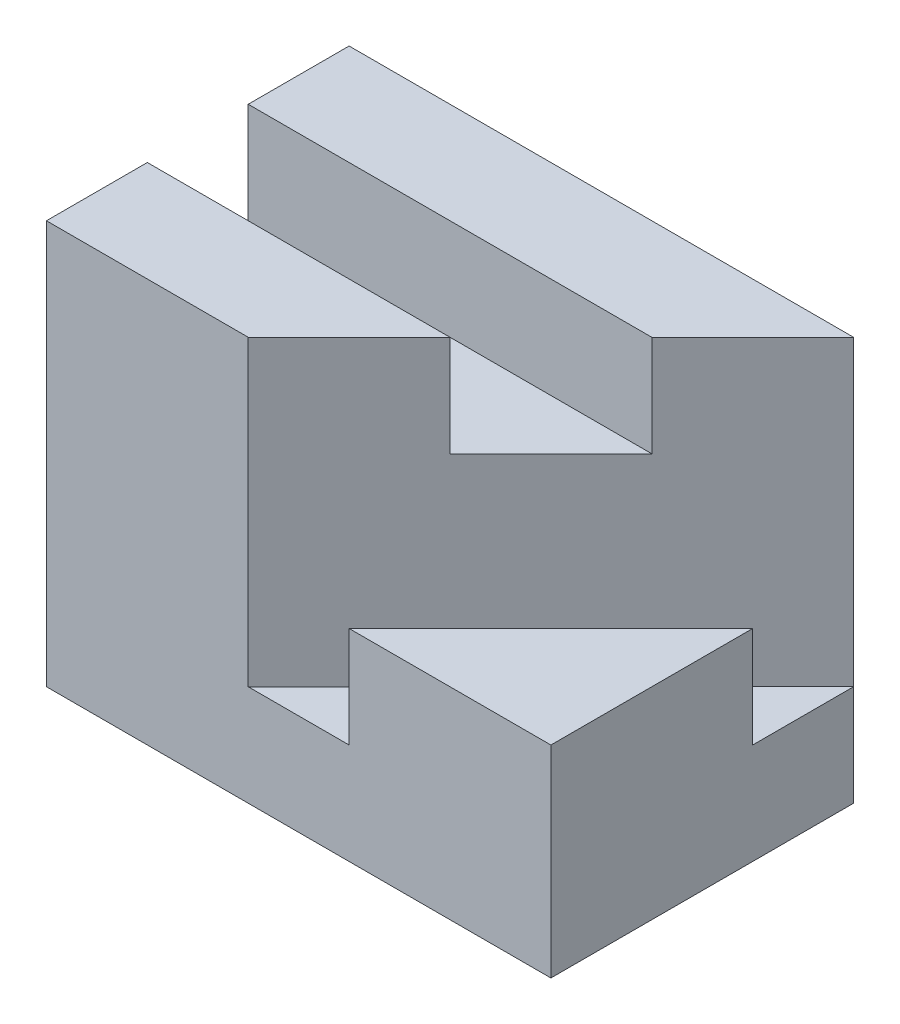
SolidWorks part; units mm, degrees
ref_plane "Front Plane" through (0, 0, 0) normal (0, 0, 1) x (1, 0, 0)
ref_plane "Top Plane" through (0, 0, 0) normal (0, 1, 0) x (1, 0, 0)
ref_plane "Right Plane" through (0, 0, 0) normal (1, 0, 0) x (0, 0, -1)
sketch "Sketch1" plane through (0, 0, 0) normal (1, 0, 0) x (0, 0, -1)
  line L0 (-23.5922, 10) -> (-23.5922, -30)
  line L1 (-23.5922, -30) -> (6.4078, -30)
  line L2 (6.4078, -30) -> (6.4078, 10)
  line L3 (6.4078, 10) -> (-3.5922, 10)
  line L4 (-3.5922, 10) -> (-3.5922, 0)
  line L5 (-3.5922, 0) -> (-13.5922, 0)
  line L6 (-13.5922, 0) -> (-13.5922, 10)
  line L7 (-13.5922, 10) -> (-23.5922, 10)
  dimension "D1" = 30
  dimension "D2" = 10
  dimension "D3" = 10
  dimension "D4" = 10
  dimension "D5" = 40
  dimension "D6" = 40
extrude "Boss-Extrude1" add sketch "Sketch1" along normal blind 50
sketch "Sketch2" plane through (0, 10, 0) normal (0, 1, 0) x (1, 0, 0)
  line L0 (50, -3.5922) -> (30, -23.5922)
  line L1 (50, -23.5922) -> (0, -23.5922) construction
  line L2 (30, -23.5922) -> (50, -23.5922)
  line L3 (50, -23.5922) -> (50, -3.5922)
  dimension "D1" = 20
extrude "Cut-Extrude1" cut sketch "Sketch2" against normal blind 20 contours L0 L2 L3
sketch "Sketch3" plane through (0, 10, 0) normal (0, 1, 0) x (1, 0, 0)
  line L0 (50, -3.5922) -> (30, -23.5922)
  line L1 (50, 6.4078) -> (20, -23.5922)
  line L2 (30, -23.5922) -> (0, -23.5922) construction
  line L3 (20, -23.5922) -> (30, -23.5922)
  line L4 (50, 6.4078) -> (50, -3.5922)
extrude "Cut-Extrude2" cut sketch "Sketch3" against normal blind 30
